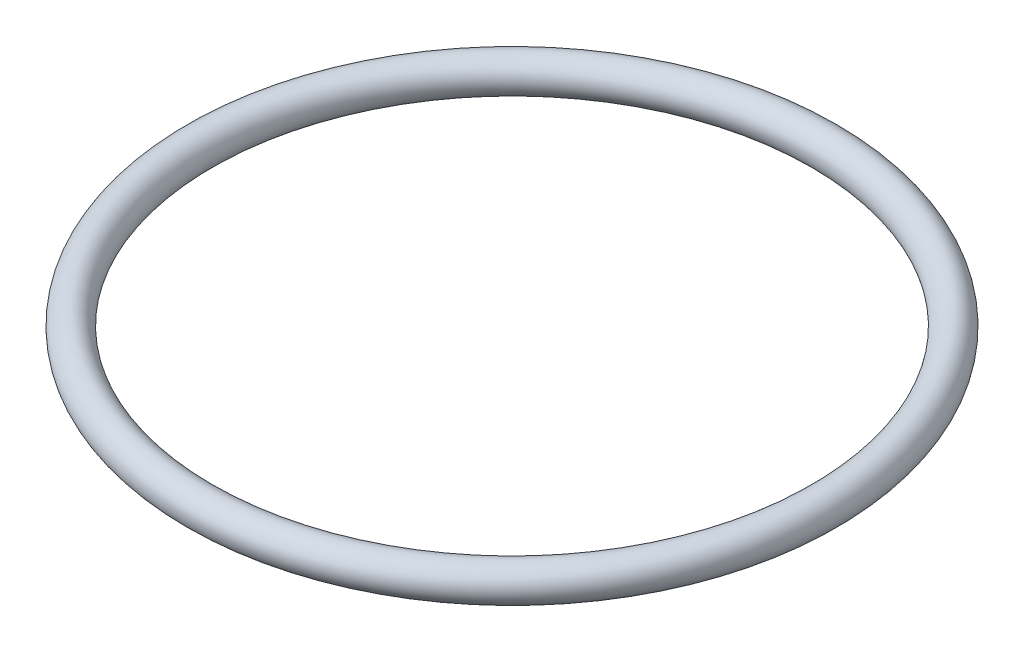
SolidWorks part; units mm, degrees
ref_plane "Plan de face" through (0, 0, 0) normal (0, 0, 1) x (1, 0, 0)
ref_plane "Plan de dessus" through (0, 0, 0) normal (0, 1, 0) x (1, 0, 0)
ref_plane "Plan de droite" through (0, 0, 0) normal (1, 0, 0) x (0, 0, -1)
sketch "Esquisse1" plane through (0, 0, 0) normal (0, 0, 1) x (1, 0, 0)
  line L0 (0, 0) -> (0, 15.6228) construction
  circle A0 centre (-22.25, 0) radius 1.25
  dimension "D1" = 2.5
  dimension "D2" = 22.25
revolve "Révolution1" add sketch "Esquisse1" angle 360 about L0
